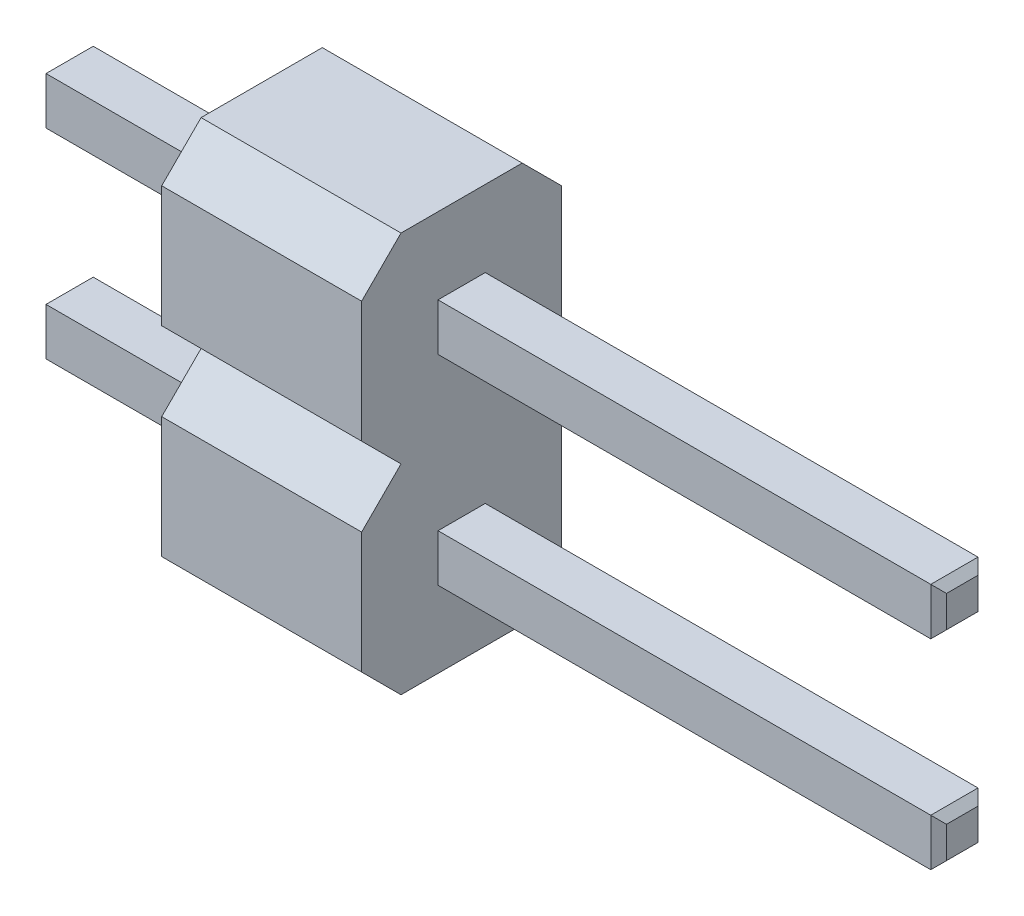
SolidWorks part; units mm, degrees
ref_plane "Front Plane" through (0, 0, 0) normal (0, 0, 1) x (1, 0, 0)
ref_plane "Top Plane" through (0, 0, 0) normal (0, 1, 0) x (1, 0, 0)
ref_plane "Right Plane" through (0, 0, 0) normal (1, 0, 0) x (0, 0, -1)
sketch "Sketch1" plane through (0, 0, 0) normal (1, 0, 0) x (0, 0, -1)
  line L0 (0, 0) -> (-1.27, 0) construction
  line L5 (-1.27, 0) -> (-1.27, 1.27) construction
  line L6 (-2.04, 1.27) -> (-0.5, 1.27)
  line L7 (-0.5, 1.27) -> (0, 0.77)
  line L8 (0, 0.77) -> (0, -0.77)
  line L9 (-2.54, 0.77) -> (-2.54, -0.77)
  line L10 (-2.04, 1.27) -> (-2.54, 0.77)
  line L11 (-0.5, -1.27) -> (0, -0.77)
  line L12 (-2.04, -1.27) -> (-0.5, -1.27)
  line L13 (-2.04, -1.27) -> (-2.54, -0.77)
  point P13 (-2.54, 0)
  dimension "D1" = 1.27
  dimension "D2" = 45
  dimension "D3" = 0.5
extrude "Plastic" add sketch "Sketch1" along normal blind 2.54
sketch "Sketch2" plane through (0, 0, 0) normal (0, 1, 0) x (1, 0, 0)
  line L0 (-2.54, -0.97) -> (-2.54, -1.57)
  line L1 (-2.54, -1.27) -> (8.9, -1.27) construction
  line L2 (0, -2.04) -> (0, -0.5) construction
  line L4 (-2.54, -1.57) -> (8.9, -1.57)
  line L6 (-2.54, -0.97) -> (8.9, -0.97)
  line L8 (8.9, -1.57) -> (8.9, -0.97)
  line L11 (-3.14, 3.36) -> (-3.14, -0.67) construction
  line L12 (-3.44, 3.36) -> (-3.44, -0.67) construction
  line L13 (-2.84, 3.36) -> (-2.84, -0.67) construction
  line L14 (2.54, -0.5) -> (2.54, -2.04) construction
  arc A3 (-3.44, -0.67) -> (-2.54, -1.57) centre (-2.54, -0.67) ccw construction
  arc A4 (-3.14, -0.67) -> (-2.54, -1.27) centre (-2.54, -0.67) ccw construction
  arc A5 (-2.84, -0.67) -> (-2.54, -0.97) centre (-2.54, -0.67) ccw construction
  point P5 (0, -1.27)
  dimension "D1" = 5.08
  dimension "D4" = 8.9
  dimension "D2" = 0.3
  dimension "D3" = 0.3
extrude "Contact" add sketch "Sketch2" along normal mid plane 0.6
chamfer "Chamfer1" distance 0.1 angle 45 8 edges at (8.9, 0.3, 1.27) (8.9, 0, 1.57) (8.9, -0.3, 1.27) (8.9, 0, 0.97) (-2.54, -0.3, 1.27) (-2.54, 0, 0.97) (-2.54, 0.3, 1.27) (-2.54, 0, 1.57)
pattern_linear "LPattern1" count 2 spacing 2.54 along (0, 1, 0) of "Plastic", "Contact", "Chamfer1"
